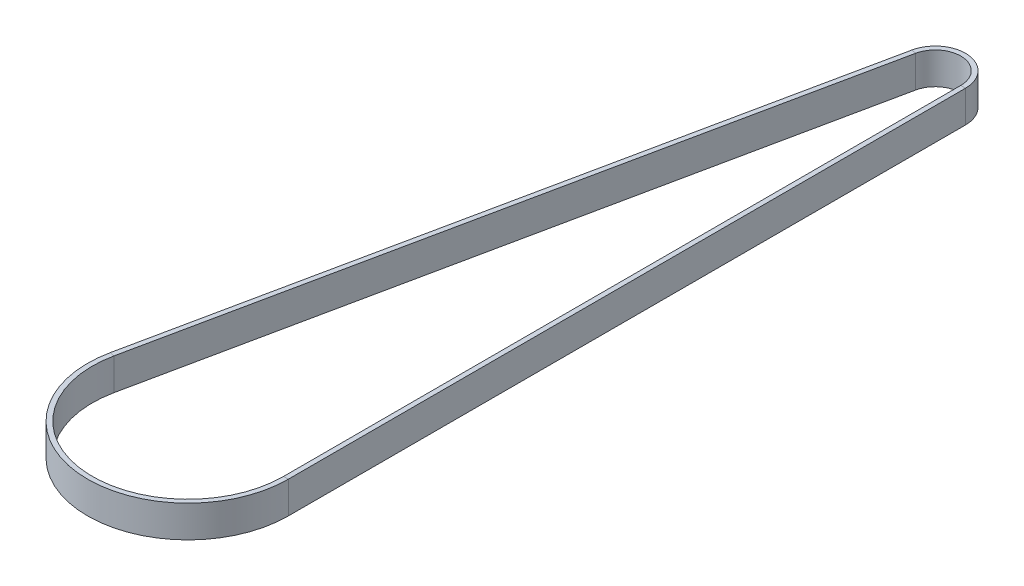
SolidWorks part; units mm, degrees
ref_plane "前视基准面" through (0, 0, 0) normal (0, 0, 1) x (1, 0, 0)
ref_plane "上视基准面" through (0, 0, 0) normal (0, 1, 0) x (1, 0, 0)
ref_plane "右视基准面" through (0, 0, 0) normal (1, 0, 0) x (0, 0, -1)
other "Configuration Table"
sketch "草图2" plane through (0, 0, 0) normal (0, 1, 0) x (1, 0, 0)
  line L0 (8, -212.5) -> (8, 0)
  line L1 (0, 0) -> (-22, 0) construction
  line L2 (0, 0) -> (0, -212.5) construction
  line L3 (0, -212.5) -> (-22, -212.5) construction
  line L4 (-22, 0) -> (-22, -212.5) construction
  line L5 (-51.3637, -206.3541) -> (-7.8303, 1.6389)
  arc A0 (8, 0) -> (-7.8303, 1.6389) centre (0, 0) ccw
  arc A1 (-51.3637, -206.3541) -> (8, -212.5) centre (-22, -212.5) ccw
  dimension "D1" = 16
  dimension "D4" = 60
  dimension "D2" = 212.5
  dimension "D3" = 22
sketch "草图3" plane through (0, 0, 0) normal (0, 0, 1) x (1, 0, 0)
  line L1 (8, 0) -> (9.5, 0)
  line L2 (8, 0) -> (8, 10)
  line L3 (8, 10) -> (9.5, 10)
  line L4 (9.5, 0) -> (9.5, 10)
  dimension "D1" = 10
  dimension "D2" = 1.5
sweep "扫描1" add profiles "草图3" path "草图2"
